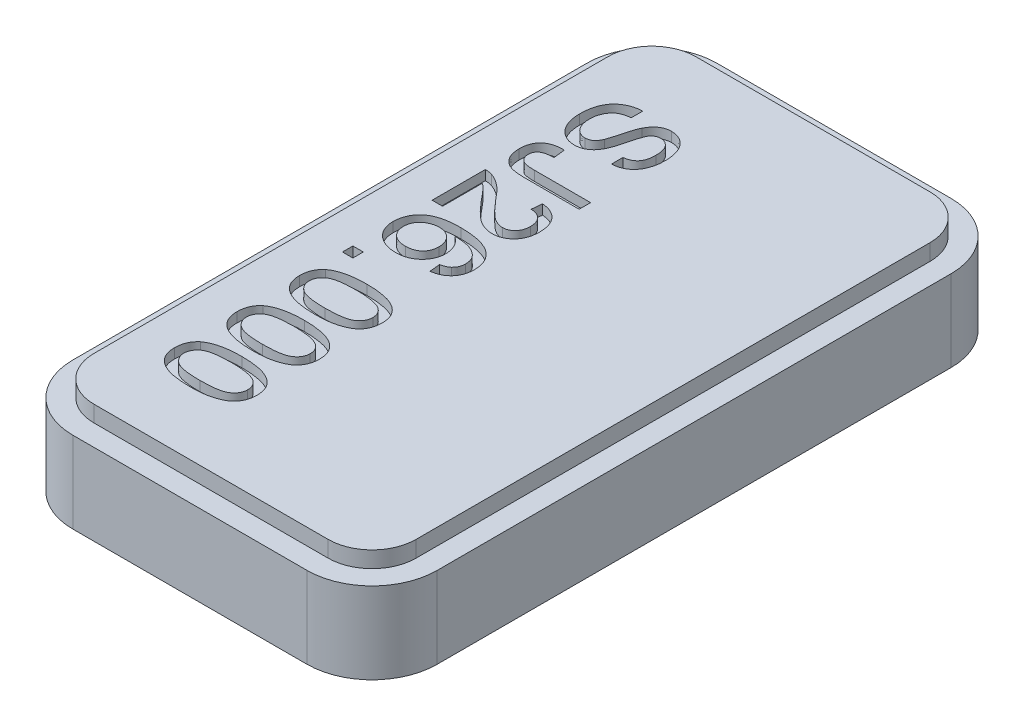
SolidWorks part; units mm, degrees
ref_plane "Front Plane" through (0, 0, 0) normal (0, 0, 1) x (1, 0, 0)
ref_plane "Top Plane" through (0, 0, 0) normal (0, 1, 0) x (1, 0, 0)
ref_plane "Right Plane" through (0, 0, 0) normal (1, 0, 0) x (0, 0, -1)
sketch "Sketch1" plane through (0, 0, 0) normal (0, 1, 0) x (1, 0, 0)
  line L1 (-0.9144, 2.5146) -> (0.9144, 2.5146)
  line L2 (-1.4224, 2.0066) -> (-1.4224, -2.0066)
  line L3 (-0.9144, -2.5146) -> (0.9144, -2.5146)
  line L4 (1.4224, 2.0066) -> (1.4224, -2.0066)
  arc A0 (-1.4224, 2.0066) -> (-0.9144, 2.5146) centre (-0.9144, 2.0066) cw
  arc A1 (0.9144, 2.5146) -> (1.4224, 2.0066) centre (0.9144, 2.0066) cw
  arc A2 (1.4224, -2.0066) -> (0.9144, -2.5146) centre (0.9144, -2.0066) cw
  arc A3 (-0.9144, -2.5146) -> (-1.4224, -2.0066) centre (-0.9144, -2.0066) cw
  point P1 (-1.4224, 0)
  point P2 (0, -2.5146)
  dimension "D1" = 0.508
  dimension "D2" = 5.0292
  dimension "D3" = 2.8448
extrude "Boss-Extrude1" add sketch "Sketch1" along normal blind 0.635
sketch "Sketch2" plane through (0, 0.635, 0) normal (0, 1, 0) x (1, 0, 0)
  line L0 (-0.9144, 2.3495) -> (-0.9144, 2.5146) construction
  line L1 (-0.9144, 2.3495) -> (0.9144, 2.3495)
  line L2 (-1.2573, 2.0066) -> (-1.2573, -2.0066)
  line L3 (-0.9144, -2.3495) -> (0.9144, -2.3495)
  line L4 (1.2573, 2.0066) -> (1.2573, -2.0066)
  line L5 (0.9144, 2.5146) -> (-0.9144, 2.5146) construction
  line L7 (-1.4224, 2.0066) -> (-1.4224, -2.0066) construction
  line L8 (-1.4224, 2.0066) -> (-1.2573, 2.0066) construction
  arc A0 (-1.2573, 2.0066) -> (-0.9144, 2.3495) centre (-0.9144, 2.0066) cw
  arc A1 (0.9144, 2.3495) -> (1.2573, 2.0066) centre (0.9144, 2.0066) cw
  arc A2 (-0.9144, -2.3495) -> (-1.2573, -2.0066) centre (-0.9144, -2.0066) cw
  arc A3 (0.9144, -2.3495) -> (1.2573, -2.0066) centre (0.9144, -2.0066) ccw
  point P0 (0, -2.3495)
  point P1 (-1.2573, 0)
  dimension "D1" = 4.699
extrude "Boss-Extrude2" add sketch "Sketch2" along normal blind 0.127
sketch "Sketch3" plane through (0, 0.762, 0) normal (0, 1, 0) x (1, 0, 0)
  line L0 (-0.9732, 1.8784) -> (-0.9732, -1.9609) construction
  text T0 "SJ26.000" height 0.635
  point P3 (-0.7766, 1.8784)
  point P4 (-0.8204, -1.9609)
extrude "Cut-Extrude1" cut sketch "Sketch3" against normal blind 0.0762
